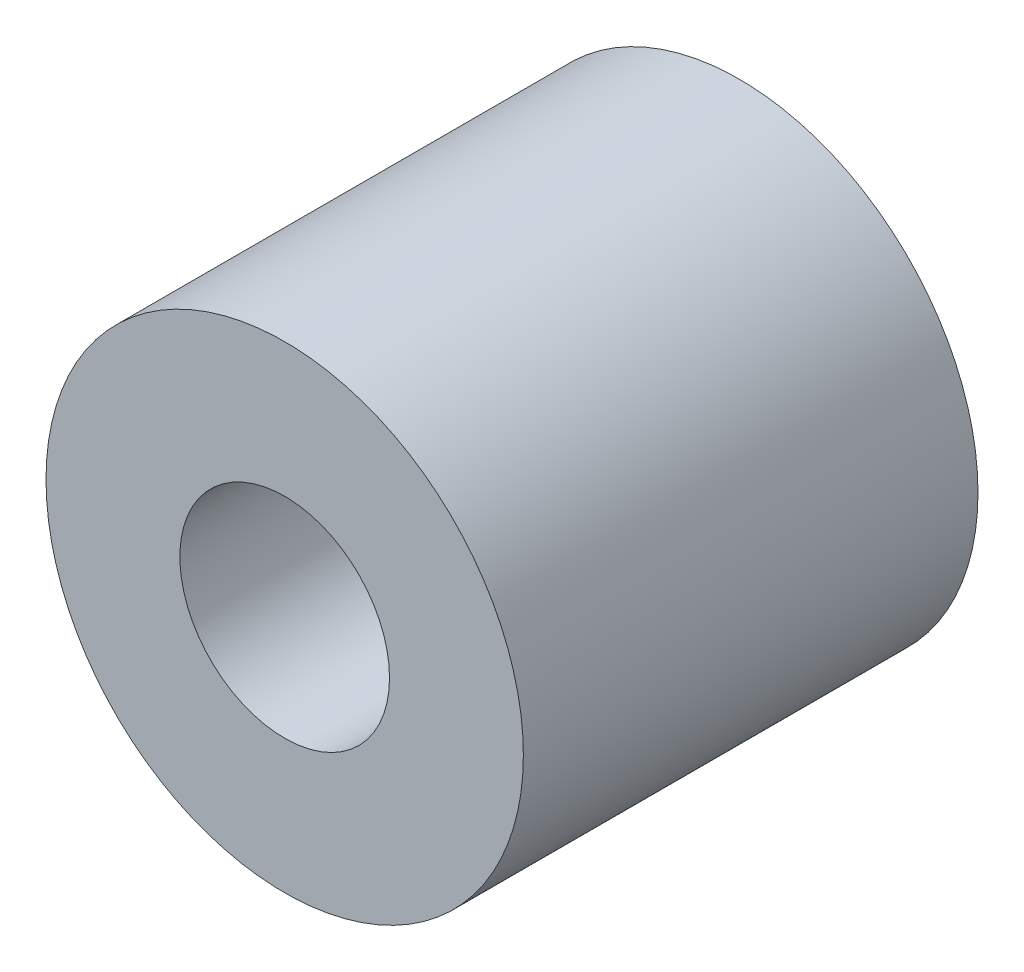
SolidWorks part; units mm, degrees
ref_plane "Front Plane" through (0, 0, 0) normal (0, 0, 1) x (1, 0, 0)
ref_plane "Top Plane" through (0, 0, 0) normal (0, 1, 0) x (1, 0, 0)
ref_plane "Right Plane" through (0, 0, 0) normal (1, 0, 0) x (0, 0, -1)
sketch "Sketch1" plane through (0, 0, 0) normal (0, 0, 1) x (1, 0, 0)
  circle A0 centre (0, 0) radius 9.45
  circle A1 centre (0, 0) radius 4.15
  dimension "D1" = 18.9
  dimension "D2" = 8.3
extrude "Boss-Extrude1" add sketch "Sketch1" along normal blind 18
